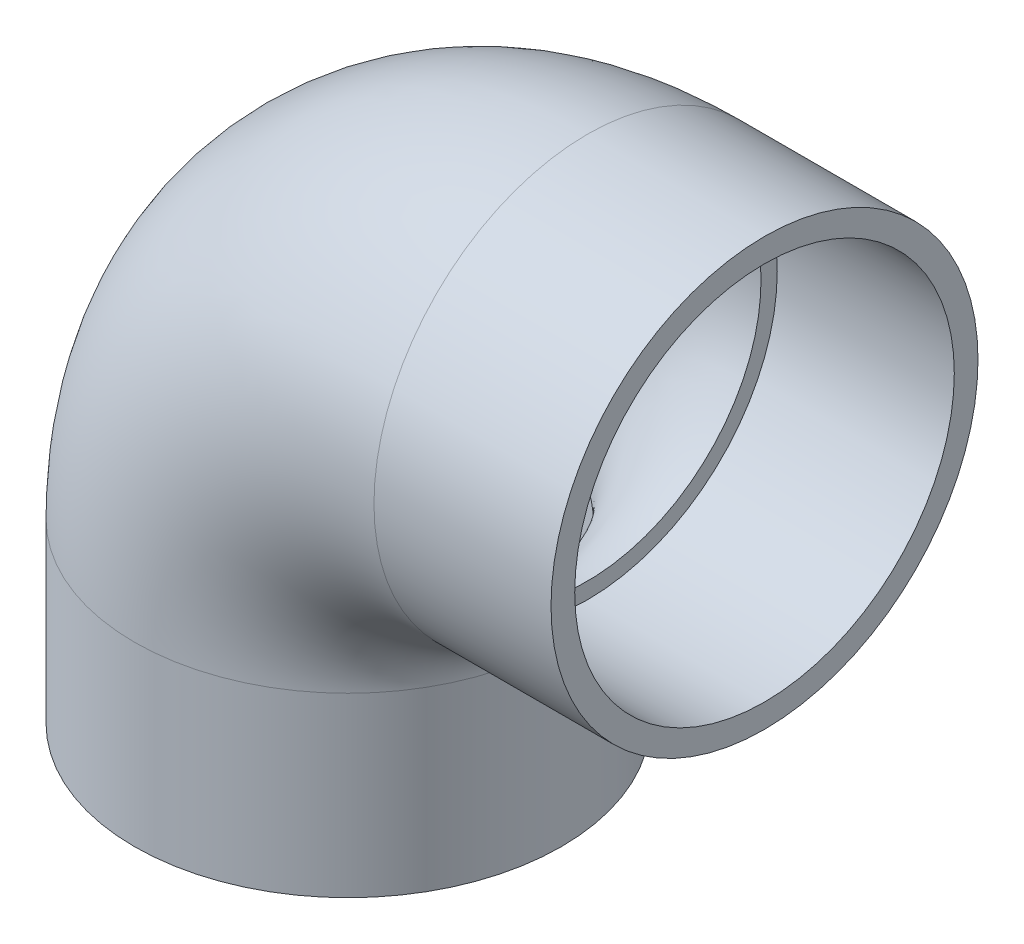
SolidWorks part; units mm, degrees
material "PVC Rígido"
ref_plane "Alzado" through (0, 0, 0) normal (0, 0, 1) x (1, 0, 0)
ref_plane "Planta" through (0, 0, 0) normal (0, 1, 0) x (1, 0, 0)
ref_plane "Vista lateral" through (0, 0, 0) normal (1, 0, 0) x (0, 0, -1)
sketch "Croquis1" plane through (0, 0, 0) normal (0, 0, 1) x (1, 0, 0)
  line L0 (0, 0) -> (0, 102)
  line L1 (138, 240) -> (240, 240)
  arc A0 (0, 102) -> (138, 240) centre (138, 102) cw
  dimension "D1" = 138
  dimension "D2" = 102
  dimension "D3" = 102
sketch "Croquis2" plane through (0, 0, 0) normal (0, 1, 0) x (1, 0, 0)
  circle A0 centre (0, 0) radius 123
  circle A1 centre (0, 0) radius 100
  dimension "D1" = 246
  dimension "D2" = 200
sweep "Barrer1" add profiles "Croquis2" path "Croquis1"
sketch "Croquis3" plane through (0, 0, 0) normal (0, -1, 0) x (1, 0, 0)
  circle A0 centre (0, 0) radius 109.35
  circle A1 centre (0, 0) radius 100
  dimension "D1" = 200
  dimension "D2" = 218.7
extrude "Cortar-Extruir1" cut sketch "Croquis3" against normal blind 102
sketch "Croquis4" plane through (240, 0, 0) normal (1, 0, 0) x (0, 0, -1)
  circle A0 centre (0, 240) radius 100
  circle A1 centre (0, 240) radius 109.35
  dimension "D1" = 200
  dimension "D2" = 218.7
extrude "Cortar-Extruir2" cut sketch "Croquis4" against normal blind 102
